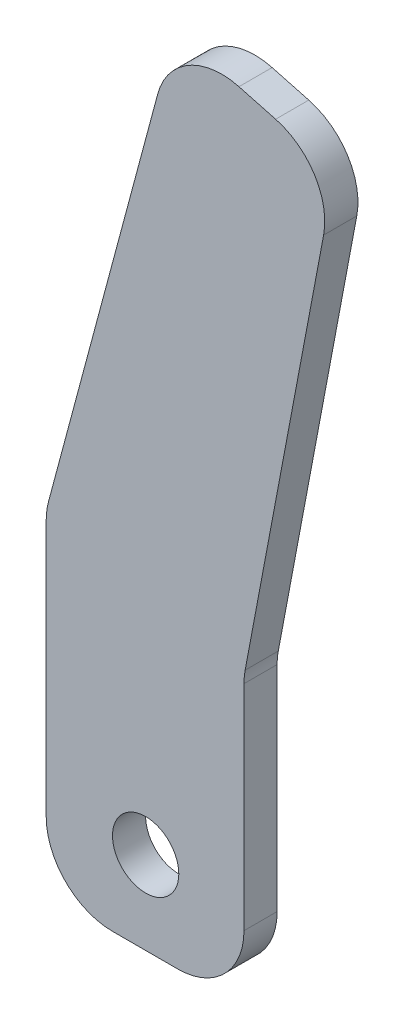
SolidWorks part; units mm, degrees
ref_plane "Front Plane" through (0, 0, 0) normal (0, 0, 1) x (1, 0, 0)
ref_plane "Top Plane" through (0, 0, 0) normal (0, 1, 0) x (1, 0, 0)
ref_plane "Right Plane" through (0, 0, 0) normal (1, 0, 0) x (0, 0, -1)
sketch "Sketch1" plane through (0, 0, 0) normal (0, 0, 1) x (1, 0, 0)
  line L0 (0, 10) -> (3.8823, 24.4889)
  line L1 (0, 0) -> (5.9659, 0)
  line L2 (0, 0) -> (0, 10)
  line L3 (5.9659, 8.6395) -> (5.9659, 8.0278)
  line L4 (5.9659, 0) -> (5.9659, 8.0278)
  line L6 (3.8823, 24.4889) -> (8.7119, 23.1948)
  line L7 (8.7119, 23.1948) -> (5.9659, 8.6395)
  circle A0 centre (2.9998, 2.5) radius 1
  dimension "D1" = 15
  dimension "D2" = 5
extrude "Boss-Extrude1" add sketch "Sketch1" along normal blind 1
fillet "Fillet1" radius 2 1 edges at (5.9659, 0, 0.5)
fillet "Fillet2" radius 2 1 edges at (0, 0, 0.5)
fillet "Fillet3" radius 2 1 edges at (8.7119, 23.1948, 0.5)
fillet "Fillet4" radius 2 1 edges at (3.8823, 24.4889, 0.5)
fillet "Fillet5" radius 2 1 edges at (0, 10, 0.5)
fillet "Fillet6" radius 2 1 edges at (5.9659, 8.6395, 0.5)
